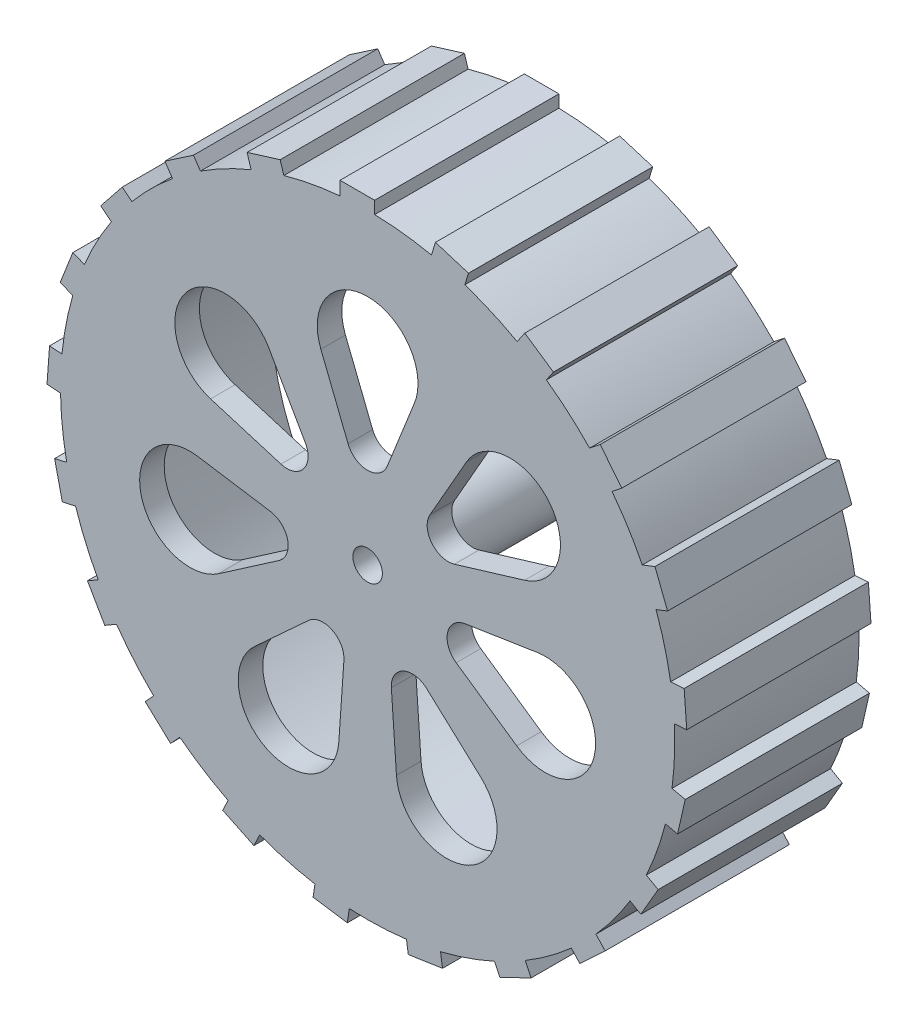
SolidWorks part; units mm, degrees
material "Rubber"
ref_plane "Front Plane" through (0, 0, 0) normal (0, 0, 1) x (1, 0, 0)
ref_plane "Top Plane" through (0, 0, 0) normal (0, 1, 0) x (1, 0, 0)
ref_plane "Right Plane" through (0, 0, 0) normal (1, 0, 0) x (0, 0, -1)
sketch "Sketch1" plane through (0, 0, 0) normal (0, 0, 1) x (1, 0, 0)
  circle A0 centre (-561.0181, 339.4055) radius 125
  circle A1 centre (-561.0181, 339.4055) radius 6
  dimension "D1" = 250
  dimension "D2" = 12
extrude "Boss-Extrude1" add sketch "Sketch1" along normal blind 75
shell "Shell1" thickness 10
sketch "Sketch2" plane through (0, 0, 75) normal (0, 0, 1) x (1, 0, 0)
  line L1 (-572.2459, 469.4275) -> (-558.1672, 469.4275)
  line L2 (-572.2459, 469.4275) -> (-572.2459, 459.2431)
  line L3 (-572.2459, 459.2431) -> (-558.1672, 459.2431)
  line L4 (-558.1672, 469.4275) -> (-558.1672, 459.2431)
  line L5 (-572.2459, 469.4275) -> (-558.1672, 459.2431) construction
  line L6 (-572.2459, 459.2431) -> (-558.1672, 469.4275) construction
  circle A0 centre (-561.0181, 339.4055) radius 125 construction
  point P0 (-565.2066, 464.3353)
extrude "Boss-Extrude2" add sketch "Sketch2" against normal up to surface (75 mm away) up to face at (-446.0181, 339.4055, 0)
pattern_circular "CirPattern1" count 21 over 360 about axis through (-561.0181, 339.4055, 0) along (0, 0, 1) of "Boss-Extrude2"
sketch "Sketch3" plane through (0, 0, 75) normal (0, 0, 1) x (1, 0, 0)
  line L0 (-561.0181, 339.4055) -> (-561.0181, 469.4275) construction
  line L1 (-558.1672, 469.4275) -> (-572.2459, 469.4275) construction
  line L2 (-580.0547, 405.9766) -> (-568.9838, 378.195)
  line L3 (-541.9816, 405.9766) -> (-553.0525, 378.195)
  arc A0 (-580.0547, 405.9766) -> (-541.9816, 405.9766) centre (-561.0181, 413.5626) cw
  arc A1 (-568.9838, 378.195) -> (-553.0525, 378.195) centre (-561.0181, 381.3693) ccw
extrude "Cut-Extrude1" cut sketch "Sketch3" against normal up to next
pattern_circular "CirPattern2" count 7 over 360 about axis through (-561.0181, 339.4055, 0) along (0, 0, 1) of "Cut-Extrude1"
